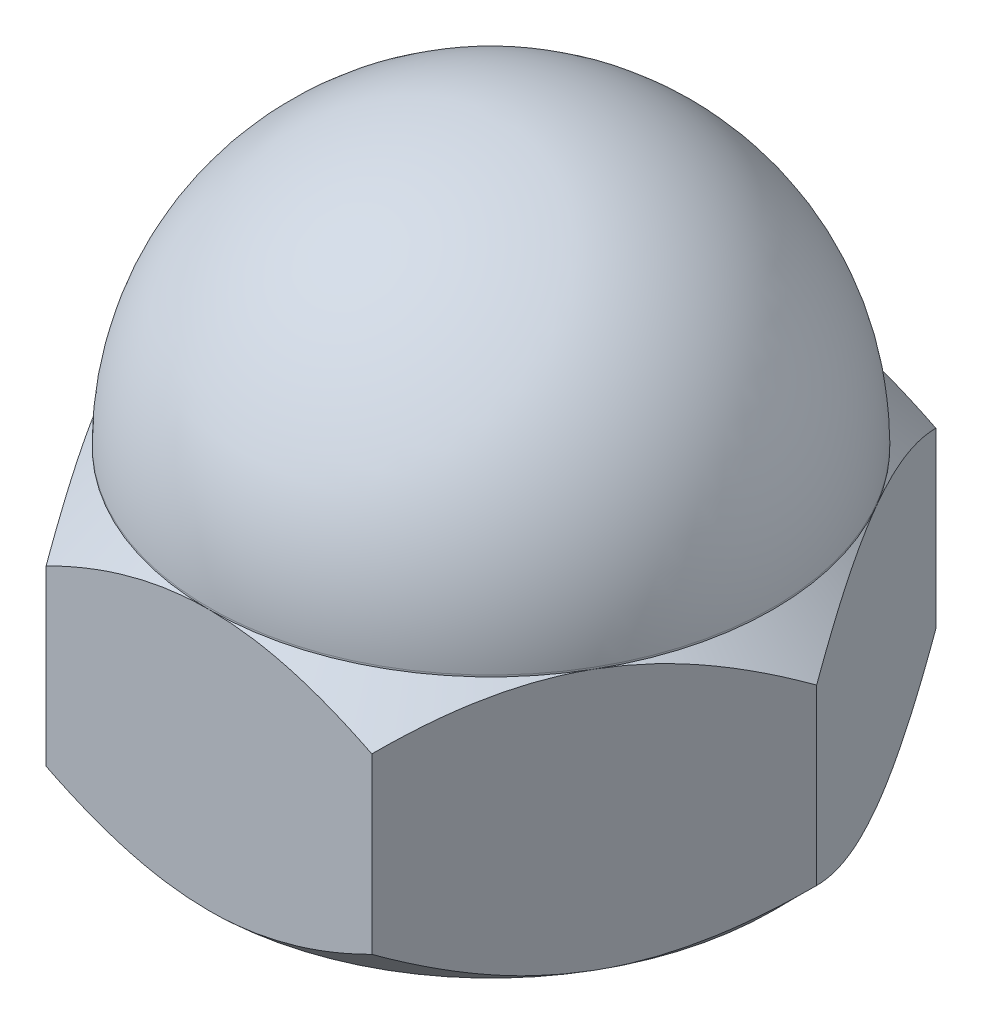
SolidWorks part; units mm, degrees
material "1023 Carbon Steel Sheet (SS)"
ref_plane "Front Plane" through (0, 0, 0) normal (0, 0, 1) x (1, 0, 0)
ref_plane "Top Plane" through (0, 0, 0) normal (0, 1, 0) x (1, 0, 0)
ref_plane "Right Plane" through (0, 0, 0) normal (1, 0, 0) x (0, 0, -1)
sketch "Sketch1" plane through (0, 0, 0) normal (0, 1, 0) x (1, 0, 0)
  line L1 (19.975, 0) -> (9.9875, 17.2989)
  line L2 (9.9875, 17.2989) -> (-9.9875, 17.2989)
  line L3 (-9.9875, 17.2989) -> (-19.975, 0)
  line L4 (-19.975, 0) -> (-9.9875, -17.2989)
  line L5 (-9.9875, -17.2989) -> (9.9875, -17.2989)
  line L6 (9.9875, -17.2989) -> (19.975, 0)
  circle A0 centre (0, 0) radius 17.2989 construction
  point P1 (0, 0)
  dimension "D1" = 39.95
extrude "Boss-Extrude1" add sketch "Sketch1" along normal blind 16 contours L2 L3 L4 L5 L6 L1
sketch "Sketch2" plane through (0, 0, 0) normal (-1, 0, 0) x (0, 0, 1)
  line L2 (-17.2989, 16) -> (-17.2989, 16.1011)
  line L3 (0, 16) -> (17.2989, 16) construction
  line L4 (-17.2989, 16) -> (0, 16)
  line L6 (0, 16) -> (0, 33.4)
  arc A0 (-17.2989, 16.1011) -> (0, 33.4) centre (0, 16.1011) cw
  point P0 (-1.8118, 17.8638)
  dimension "D2" = 33.4
revolve "Revolve1" add sketch "Sketch2" angle 360 about L6
hole_wizard "Ø1.0mm Dowel Hole1" positions "Sketch4" profile "Sketch5" hole size "Ø1.0" standard "ISO"
sketch "Sketch4" plane through (0, 0, 0) normal (0, -1, 0) x (-1, 0, 0)
  point P0 (0, 0)
sketch "Sketch5" plane through (0, 0, 0) normal (1, 0, 0) x (0, 0, -1)
  line L0 (0, 0) -> (0, 32.4086)
  line L1 (0, 32.4086) -> (10, 26.4)
  line L2 (10, 26.4) -> (10, 0)
  line L5 (10, 0) -> (0, 0)
  line L10 (0, 32.4086) -> (-10, 26.4) construction
  line L11 (0, -6.35) -> (0, 107.95) construction
  dimension "Hole Dia." = 20
  dimension "Hole Depth" = 26.4
  dimension "Drill Angle" = 118
sketch "Sketch6" plane through (0, 0, 0) normal (0, 0, 1) x (1, 0, 0)
  line L0 (17.2989, 16) -> (19.975, 13.3239)
  line L1 (19.975, 16) -> (19.975, 0) construction
  line L2 (19.975, 13.3239) -> (19.975, 16)
  line L3 (19.975, 16) -> (17.2989, 16)
  line L4 (-19.975, 16) -> (-19.975, 0) construction
  line L5 (-1019.975, 8) -> (48980.025, 8) construction
  line L6 (19.975, 2.6761) -> (19.975, 0)
  line L7 (19.975, 0) -> (17.2989, 0)
  line L8 (17.2989, 0) -> (19.975, 2.6761)
  point P5 (-19.975, 8)
  point P15 (14, 16)
  point P16 (17.77, 16)
  dimension "D1" = 45
revolve "Cut-Revolve1" cut sketch "Sketch6" angle 360
